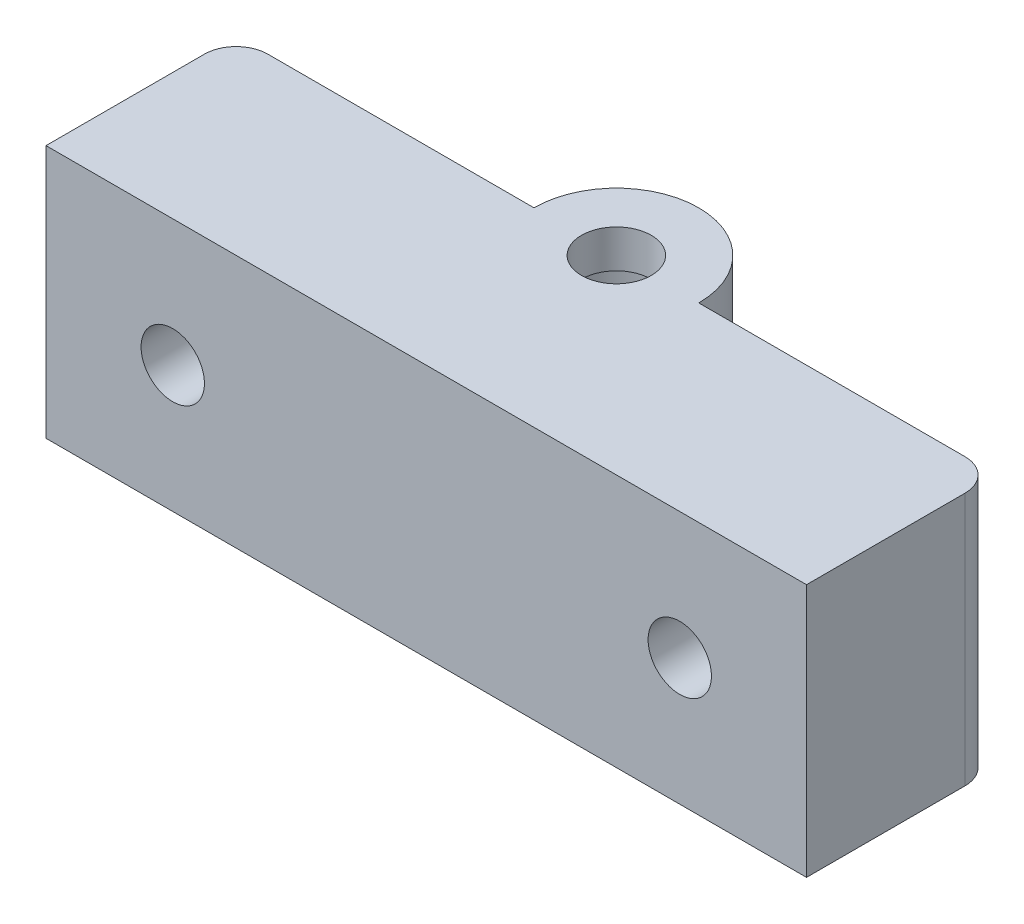
SolidWorks part; units mm, degrees
ref_plane "Plan de face" through (0, 0, 0) normal (0, 0, 1) x (1, 0, 0)
ref_plane "Plan de dessus" through (0, 0, 0) normal (0, 1, 0) x (1, 0, 0)
ref_plane "Plan de droite" through (0, 0, 0) normal (1, 0, 0) x (0, 0, -1)
sketch "Esquisse2" plane through (0, 0, 0) normal (0, 1, 0) x (1, 0, 0)
  line L0 (0, 55.5781) -> (0, -63.9089) construction
  line L1 (-58.0774, 0) -> (126.6277, 0) construction
  line L2 (20.5481, -15) -> (88.9495, -15) construction
  line L3 (-6.5, 0) -> (-27.5, 0)
  line L4 (-30, -2.5) -> (-30, -15)
  line L5 (-30, -15) -> (30, -15)
  line L6 (30, -15) -> (30, -2.5)
  line L7 (27.5, 0) -> (6.5, 0)
  arc A0 (-6.5, 0) -> (6.5, 0) centre (0, 0) cw
  circle A1 centre (0, 0) radius 2.75
  arc A2 (30, -2.5) -> (27.5, 0) centre (27.5, -2.5) ccw
  arc A3 (-27.5, 0) -> (-30, -2.5) centre (-27.5, -2.5) ccw
  point P17 (30, 0)
  point P20 (-30, 0)
  dimension "D1" = 15
  dimension "D3" = 6.5
  dimension "D4" = 5.5
  dimension "D5" = 2.5
  dimension "D2" = 60
extrude "Boss.-Extru.1" add sketch "Esquisse2" along normal blind 20
sketch "Esquisse3" plane through (0, 0, 0) normal (0, 0, -1) x (-1, 0, 0)
  line L0 (-30, 10) -> (30, 10) construction
  line L1 (0, 0) -> (0, 29.5467) construction
  line L4 (-27.5, 0) -> (-6.5, 0)
  line L5 (-6.5, 0) -> (-6.5, 20)
  line L6 (-6.5, 20) -> (-27.5, 20)
  line L7 (-27.5, 20) -> (-27.5, 0)
  line L8 (-27.5, 0) -> (-6.5, 0)
  line L9 (-6.5, 0) -> (-6.5, 20)
  line L10 (-6.5, 20) -> (-27.5, 20)
  line L12 (6.5, 0) -> (27.5, 0)
  line L13 (27.5, 0) -> (27.5, 20)
  line L14 (27.5, 20) -> (6.5, 20)
  line L15 (6.5, 20) -> (6.5, 0)
  line L16 (6.5, 0) -> (27.5, 0)
  line L18 (27.5, 20) -> (6.5, 20)
  line L19 (6.5, 20) -> (6.5, 0)
  line L22 (-27.5, 20) -> (-27.5, 0)
  line L23 (27.5, 0) -> (27.5, 20)
  circle A0 centre (-20, 10) radius 2.5
  circle A1 centre (20, 10) radius 2.5
  dimension "D3" = 5
  dimension "D4" = 20
  dimension "D5" = 10
  dimension "D1" = 0
  dimension "D2" = 0
extrude "Enlèv. mat.-Extru.1" cut sketch "Esquisse3" against normal blind 20 contours A0 | A1
sketch "Esquisse4" plane through (0, 0, 0) normal (0, -1, 0) x (1, 0, 0)
  line L5 (6.5, 0) -> (27.5, 0)
  line L6 (30, 2.5) -> (30, 15)
  line L7 (30, 15) -> (-30, 15)
  line L8 (-30, 15) -> (-30, 2.5)
  line L9 (-27.5, 0) -> (-6.5, 0)
  line L10 (6.5, 0) -> (27.5, 0)
  line L11 (30, 2.5) -> (30, 15)
  line L12 (30, 15) -> (-30, 15)
  line L13 (-30, 15) -> (-30, 2.5)
  line L14 (-27.5, 0) -> (-6.5, 0)
  circle A0 centre (0, 0) radius 2.75 construction
  circle A1 centre (0, 0) radius 2.75
  circle A2 centre (0, 0) radius 5
  arc A3 (-6.5, 0) -> (6.5, 0) centre (0, 0) ccw
  arc A4 (27.5, 0) -> (30, 2.5) centre (27.5, 2.5) ccw
  arc A5 (-30, 2.5) -> (-27.5, 0) centre (-27.5, 2.5) ccw
  arc A6 (-6.5, 0) -> (6.5, 0) centre (0, 0) ccw
  arc A7 (27.5, 0) -> (30, 2.5) centre (27.5, 2.5) ccw
  arc A8 (-30, 2.5) -> (-27.5, 0) centre (-27.5, 2.5) ccw
  circle M17 centre (0, 0) radius 2.75
  dimension "D2" = 10
  dimension "D1" = 0
extrude "Enlèv. mat.-Extru.2" cut sketch "Esquisse4" against normal blind 17 contours A2 M17
